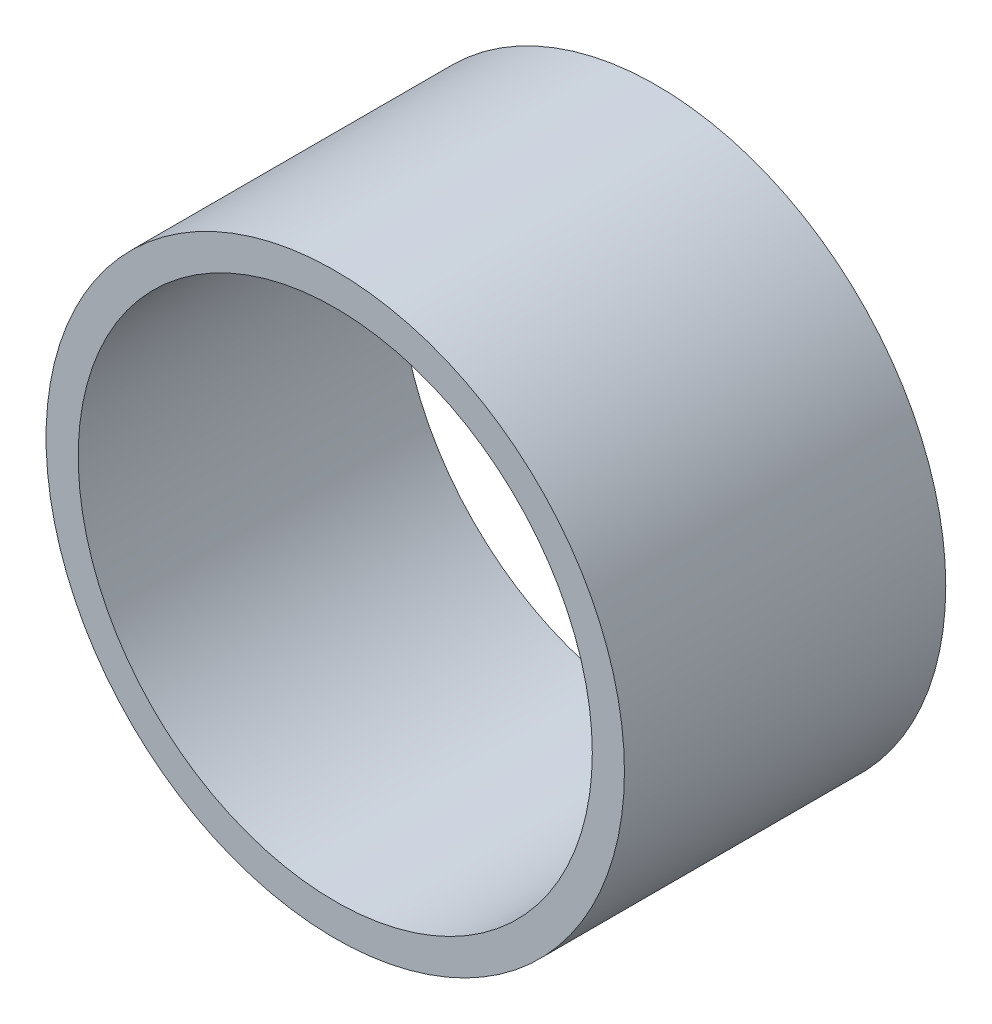
SolidWorks part; units mm, degrees
ref_plane "Ön Düzlem" through (0, 0, 0) normal (0, 0, 1) x (1, 0, 0)
ref_plane "Üst Düzlem" through (0, 0, 0) normal (0, 1, 0) x (1, 0, 0)
ref_plane "Sağ Düzlem" through (0, 0, 0) normal (1, 0, 0) x (0, 0, -1)
sketch "Çizim1" plane through (0, 0, 0) normal (0, 0, 1) x (1, 0, 0)
  circle A0 centre (0, 0) radius 4
  circle A1 centre (0, 0) radius 4.5
  dimension "D1" = 9
  dimension "D2" = 8
extrude "Yükseklik-Ekstrüzyon2" add sketch "Çizim1" along normal blind 5
